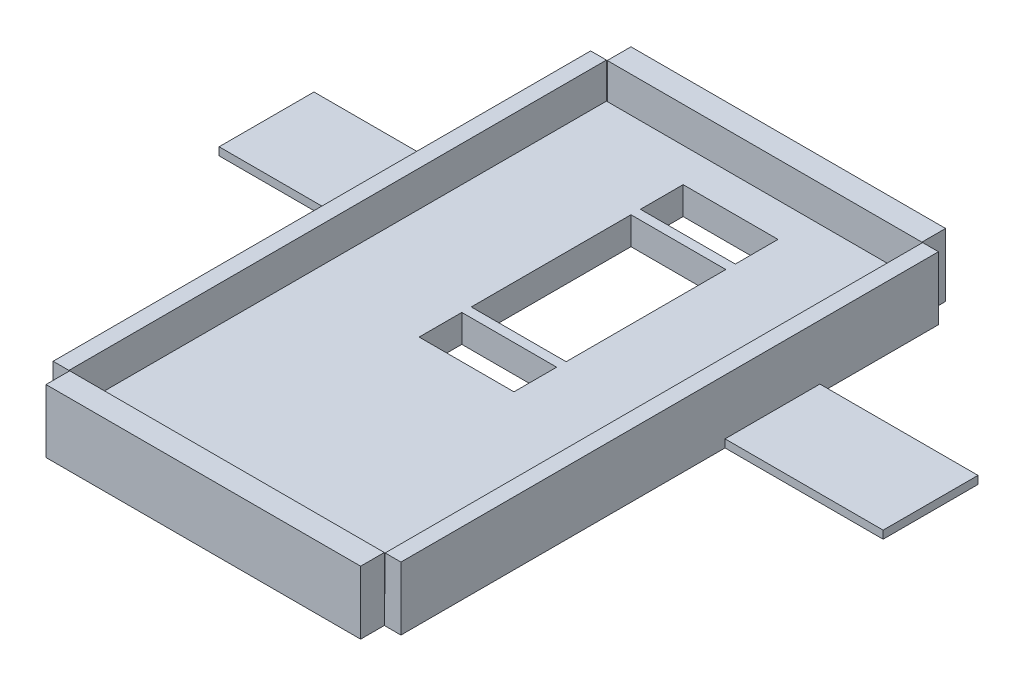
SolidWorks part; units mm, degrees
ref_plane "Front Plane" through (0, 0, 0) normal (0, 0, 1) x (1, 0, 0)
ref_plane "Top Plane" through (0, 0, 0) normal (0, 1, 0) x (1, 0, 0)
ref_plane "Right Plane" through (0, 0, 0) normal (1, 0, 0) x (0, 0, -1)
sketch "Sketch2" plane through (0, 0, 0) normal (0, 1, 0) x (1, 0, 0)
  line L0 (0, 17) -> (0, -17)
  line L1 (-10, 17) -> (10, 17)
  line L2 (-10, 17) -> (-10, -17)
  line L3 (-10, -17) -> (10, -17)
  line L4 (10, 17) -> (10, -17)
  line L5 (-10, 17) -> (10, -17) construction
  line L6 (-10, -17) -> (10, 17) construction
  line L7 (-10, 17) -> (-11.5, 17)
  line L8 (-10, 17) -> (-10, -17)
  line L9 (-10, -17) -> (-11.5, -17)
  line L10 (-11.5, 17) -> (-11.5, -17)
  line L11 (10, -17) -> (11.5, -17)
  line L12 (11.5, 17) -> (11.5, -17)
  line L13 (10, 17) -> (11.5, 17)
  line L14 (10, 17) -> (10, -17)
  line L15 (-10, 0) -> (10, 0)
  line L16 (-10, 17) -> (10, 17)
  line L17 (-10, 17) -> (-10, 18.5)
  line L18 (-10, 18.5) -> (10, 18.5)
  line L19 (10, 17) -> (10, 18.5)
  line L20 (-10, -18.5) -> (10, -18.5)
  line L21 (10, -17) -> (10, -18.5)
  line L22 (-10, -17) -> (10, -17)
  line L23 (-10, -17) -> (-10, -18.5)
  line L24 (0, 17) -> (0, 13.5)
  line L25 (0, 13.5) -> (0, 6.5)
  line L26 (-3, 14.85) -> (3, 14.85)
  line L27 (-3, 14.85) -> (-3, 12.15)
  line L28 (-3, 12.15) -> (3, 12.15)
  line L29 (3, 14.85) -> (3, 12.15)
  line L30 (-3, 14.85) -> (3, 12.15) construction
  line L31 (-3, 12.15) -> (3, 14.85) construction
  line L32 (0, 6.5) -> (0, -0.5)
  line L33 (-3, 11.55) -> (3, 11.55)
  line L34 (-3, 11.55) -> (-3, 1.45)
  line L35 (-3, 1.45) -> (3, 1.45)
  line L36 (3, 11.55) -> (3, 1.45)
  line L37 (-3, 11.55) -> (3, 1.45) construction
  line L38 (-3, 1.45) -> (3, 11.55) construction
  line L40 (-3, 0.85) -> (3, 0.85)
  line L41 (-3, 0.85) -> (-3, -1.85)
  line L42 (-3, -1.85) -> (3, -1.85)
  line L43 (3, 0.85) -> (3, -1.85)
  line L44 (-3, 0.85) -> (3, -1.85) construction
  line L45 (-3, -1.85) -> (3, 0.85) construction
  point P0 (0, 0)
  dimension "D1" = 20
  dimension "D2" = 34
  dimension "D3" = 1.5
  dimension "D4" = 1.5
  dimension "D5" = 2.7
  dimension "D6" = 6
  dimension "D7" = 10.1
  dimension "D8" = 6
  dimension "D9" = 6
  dimension "D10" = 2.7
extrude "Boss-Extrude1" add sketch "Sketch2" along normal blind 1.75 contours L41 L40 L32 L35 L34 L33 L25 L28 L27 L26 L0 L1 L2 L15 | L42 L41 L15 L8 L3 L0 | L15 L43 L42 L0 L3 L14 | L40 L43 L15 L4 L1 L0 L26 L29 L28 L25 L33 L36 L35 L32
sketch "Sketch4" plane through (0, 0, 0) normal (0, 1, 0) x (1, 0, 0)
  line L0 (0, 14.85) -> (0, 0.529)
  line L1 (-10, 17) -> (-11, 17)
  line L2 (-10, 17) -> (-10, -17)
  line L3 (-10, -17) -> (-11, -17)
  line L4 (-11, 17) -> (-11, -17)
  line L5 (-3, 14.85) -> (3, 14.85) construction
  line L6 (10, -17) -> (11, -17)
  line L7 (11, 17) -> (11, -17)
  line L8 (10, 17) -> (11, 17)
  line L9 (10, 17) -> (10, -17)
  line L10 (0, 0) -> (8.3045, 0)
  line L15 (-10, 17) -> (10, 17) construction
  line L16 (-9.95, 17) -> (9.95, 17)
  line L17 (-9.95, 17) -> (-9.95, 18.5)
  line L18 (-9.95, 18.5) -> (9.95, 18.5)
  line L19 (0, 17) -> (0, 18.5)
  line L20 (9.95, 17) -> (9.95, 18.5)
  line L21 (-9.95, -17) -> (-9.95, -18.5)
  line L22 (-9.95, -17) -> (9.95, -17)
  line L23 (9.95, -17) -> (9.95, -18.5)
  line L24 (-9.95, -18.5) -> (9.95, -18.5)
  dimension "D1" = 1
  dimension "D2" = 19.9
  dimension "D3" = 1.5
extrude "Boss-Extrude3" add sketch "Sketch4" along normal blind 4 contours L18 L20 L16 L17 | L7 L6 L9 L8 | L4 L3 L2 L1 | L24 L23 L22 L21
sketch "Sketch6" plane through (0, 0, 0) normal (0, -1, 0) x (1, 0, 0)
  line L0 (0, -14.85) -> (0, 1.85)
  line L1 (-3, -14.85) -> (3, -14.85) construction
  line L2 (-3, 1.85) -> (3, 1.85) construction
  line L3 (0, -6.5) -> (-11, -6.5)
  line L4 (-11, -17) -> (-11, 17) construction
sketch "Sketch7" plane through (-11, 0, 0) normal (-1, 0, 0) x (0, 0, 1)
  line L0 (-6.5, 0) -> (-9.5, 0)
  line L1 (-17, 0) -> (17, 0) construction
  line L3 (-9.5, 0) -> (-3.5, 0)
  line L4 (-9.5, 0) -> (-9.5, 0.5)
  line L5 (-9.5, 0.5) -> (-3.5, 0.5)
  line L6 (-3.5, 0) -> (-3.5, 0.5)
  point P8 (0, 0)
  point P9 (0, 0)
  dimension "D1" = 6
  dimension "D2" = 0.5
extrude "Boss-Extrude5" add sketch "Sketch7" along normal blind 10 contours L4 L3 L6 L5
sketch "Sketch8" plane through (0, 0, 0) normal (0, -1, 0) x (1, 0, 0)
  line L0 (3, -6.5) -> (11, -6.5)
  line L1 (3, -11.55) -> (3, -1.45) construction
  line L2 (11, -17) -> (11, 17) construction
sketch "Sketch9" plane through (11, 0, 0) normal (1, 0, 0) x (0, 0, -1)
  line L0 (6.5, 0) -> (9.5, 0)
  line L1 (17, 0) -> (-17, 0) construction
  line L2 (6.5, 0) -> (3.5, 0)
  line L4 (9.5, 0) -> (3.5, 0)
  line L5 (9.5, 0) -> (9.5, 0.5)
  line L6 (9.5, 0.5) -> (3.5, 0.5)
  line L7 (3.5, 0) -> (3.5, 0.5)
  dimension "D1" = 6
  dimension "D2" = 0.5
extrude "Boss-Extrude6" add sketch "Sketch9" along normal blind 10 contours L5 L4 L7 L6
